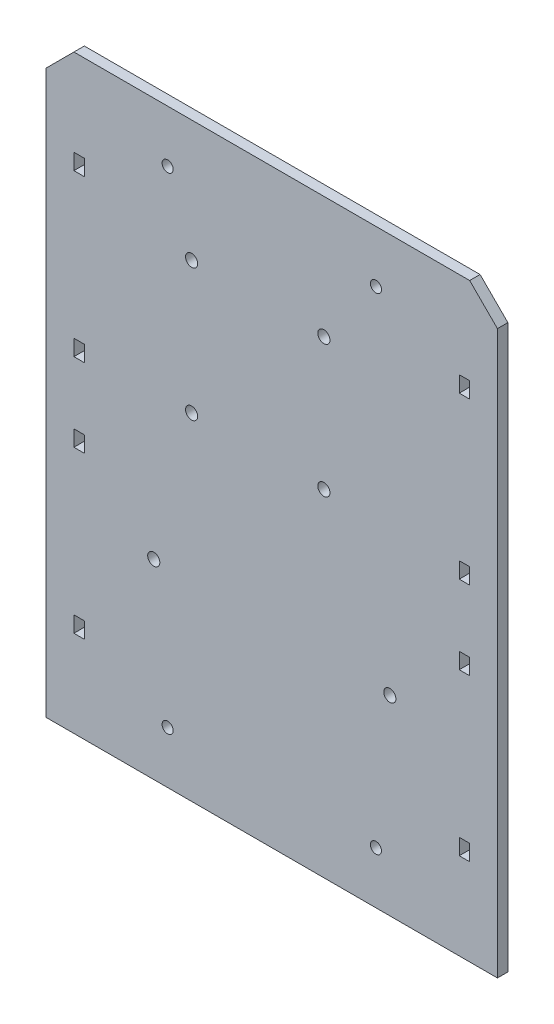
SolidWorks part; units mm, degrees
ref_plane "正面" through (0, 0, 0) normal (0, 0, 1) x (1, 0, 0)
ref_plane "平面" through (0, 0, 0) normal (0, 1, 0) x (1, 0, 0)
ref_plane "右側面" through (0, 0, 0) normal (1, 0, 0) x (0, 0, -1)
sketch "ｽｹｯﾁ1" plane through (0, 0, 0) normal (0, 0, 1) x (1, 0, 0)
  line L0 (0, 162) -> (8, 170)
  line L1 (0, 0) -> (130, 0)
  line L2 (0, 0) -> (0, 162)
  line L3 (8, 170) -> (122, 170)
  line L4 (130, 0) -> (130, 162)
  line L5 (8, 145) -> (11, 145)
  line L6 (8, 145) -> (8, 140.4)
  line L7 (8, 140.4) -> (11, 140.4)
  line L8 (11, 145) -> (11, 140.4)
  line L9 (122, 145) -> (119, 145)
  line L10 (122, 145) -> (122, 140.4)
  line L11 (122, 140.4) -> (119, 140.4)
  line L12 (119, 145) -> (119, 140.4)
  line L13 (8, 29.6) -> (11, 29.6)
  line L14 (8, 29.6) -> (8, 25)
  line L15 (8, 25) -> (11, 25)
  line L16 (11, 29.6) -> (11, 25)
  line L17 (119, 29.6) -> (122, 29.6)
  line L18 (119, 29.6) -> (119, 25)
  line L19 (119, 25) -> (122, 25)
  line L20 (122, 29.6) -> (122, 25)
  line L21 (8, 98.6) -> (11, 98.6)
  line L22 (8, 98.6) -> (8, 94)
  line L23 (8, 94) -> (11, 94)
  line L24 (11, 98.6) -> (11, 94)
  line L25 (119, 98.6) -> (122, 98.6)
  line L26 (119, 98.6) -> (119, 94)
  line L27 (119, 94) -> (122, 94)
  line L28 (122, 98.6) -> (122, 94)
  line L29 (8, 76) -> (11, 76)
  line L30 (8, 76) -> (8, 71.4)
  line L31 (8, 71.4) -> (11, 71.4)
  line L32 (11, 76) -> (11, 71.4)
  line L33 (119, 76) -> (122, 76)
  line L34 (119, 76) -> (119, 71.4)
  line L35 (119, 71.4) -> (122, 71.4)
  line L36 (122, 76) -> (122, 71.4)
  line L37 (122, 170) -> (130, 162)
  circle A0 centre (35, 155) radius 1.6
  circle A1 centre (95, 155) radius 1.6
  circle A2 centre (35, 15) radius 1.6
  circle A3 centre (95, 15) radius 1.6
  circle A4 centre (41.9, 135) radius 1.75
  circle A5 centre (80, 135) radius 1.75
  circle A6 centre (41.9, 96.9) radius 1.75
  circle A7 centre (80, 96.9) radius 1.75
  circle A8 centre (31, 55) radius 1.75
  circle A9 centre (99, 55) radius 1.75
  point P21 (119, 142.7)
  point P38 (8, 27.3)
  point P39 (9.5, 25)
  point P62 (0, 0)
  dimension "D40" = 3.2
  dimension "D41" = 3.2
  dimension "D42" = 3.2
  dimension "D43" = 3.2
  dimension "D52" = 3.5
  dimension "D53" = 3.5
  dimension "D54" = 3.5
  dimension "D55" = 3.5
  dimension "D60" = 3.5
  dimension "D61" = 3.5
  dimension "D1" = 170
  dimension "D3" = 3
  dimension "D4" = 4.6
  dimension "D5" = 3
  dimension "D6" = 4.6
  dimension "D7" = 3
  dimension "D8" = 4.6
  dimension "D9" = 3
  dimension "D10" = 4.6
  dimension "D11" = 3
  dimension "D12" = 4.6
  dimension "D13" = 3
  dimension "D14" = 4.6
  dimension "D15" = 4.6
  dimension "D16" = 3
  dimension "D17" = 3
  dimension "D18" = 4.6
  dimension "D19" = 51
  dimension "D20" = 51
  dimension "D21" = 8
  dimension "D22" = 8
  dimension "D23" = 8
  dimension "D24" = 8
  dimension "D25" = 8
  dimension "D26" = 8
  dimension "D27" = 51
  dimension "D28" = 51
  dimension "D29" = 8
  dimension "D30" = 8
  dimension "D31" = 25
  dimension "D32" = 25
  dimension "D33" = 25
  dimension "D34" = 25
  dimension "D35" = 130
  dimension "D36" = 8
  dimension "D37" = 11.3137
  dimension "D38" = 11.3137
  dimension "D39" = 45
  dimension "D44" = 35
  dimension "D45" = 35
  dimension "D46" = 35
  dimension "D47" = 35
  dimension "D48" = 140
  dimension "D49" = 140
  dimension "D50" = 15
  dimension "D51" = 15
  dimension "D56" = 38.1
  dimension "D57" = 38.1
  dimension "D58" = 35
  dimension "D59" = 50
  dimension "D62" = 68
  dimension "D63" = 31
  dimension "D64" = 55
extrude "ﾎﾞｽ - 押し出し1" add sketch "ｽｹｯﾁ1" along normal blind 3
